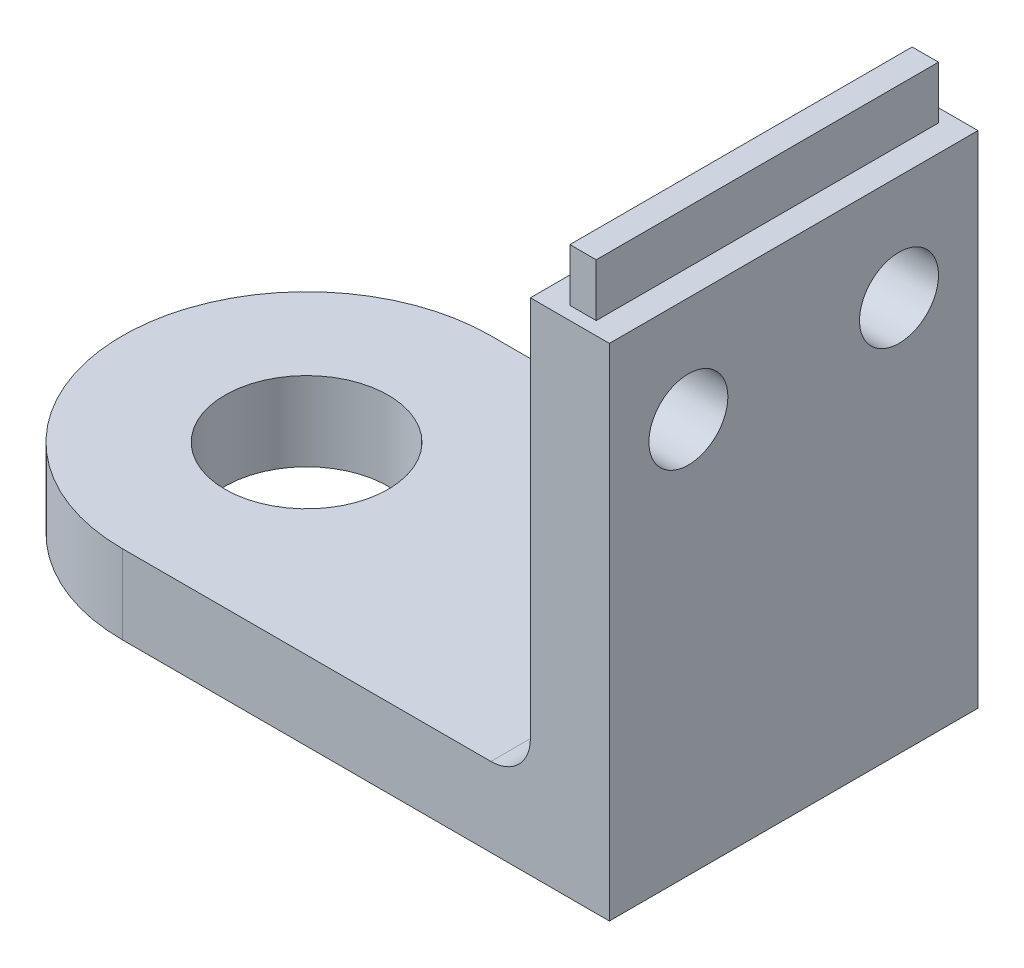
SolidWorks part; units mm, degrees
material "ABS"
ref_plane "Front Plane" through (0, 0, 0) normal (0, 0, 1) x (1, 0, 0)
ref_plane "Top Plane" through (0, 0, 0) normal (0, 1, 0) x (1, 0, 0)
ref_plane "Right Plane" through (0, 0, 0) normal (1, 0, 0) x (0, 0, -1)
ref_plane "Y-19_00" through (0, -19, 0) normal (0, 1, 0) x (1, 0, 0)
sketch "Sketch1" plane through (0, -19, 0) normal (0, 1, 0) x (1, 0, 0)
  line L0 (5.5, -7) -> (24, -7)
  line L1 (24, -7) -> (24, 7)
  line L2 (24, 7) -> (5.5, 7)
  arc A0 (5.5, 7) -> (5.5, -7) centre (5.5, 0) ccw
extrude "Boss-Extrude1" add sketch "Sketch1" along normal blind 3
sketch "Sketch2" plane through (0, 0, 0) normal (0, 0, 1) x (1, 0, 0)
  line L0 (7.7, -19) -> (-7.7, -19) construction
  line L1 (21, -19) -> (24, -19)
  line L2 (21, -19) -> (21, 0)
  line L3 (21, 0) -> (24, 0)
  line L4 (24, -19) -> (24, 0)
extrude "Boss-Extrude2" add sketch "Sketch2" along normal mid plane 14
sketch "Sketch3" plane through (0, 0, 0) normal (0, 1, 0) x (1, 0, 0)
  line L1 (22, -6.5) -> (23, -6.5)
  line L2 (22, -6.5) -> (22, 6.5)
  line L3 (22, 6.5) -> (23, 6.5)
  line L4 (23, -6.5) -> (23, 6.5)
extrude "Boss-Extrude3" add sketch "Sketch3" along normal blind 2
sketch "Sketch4" plane through (0, -19, 0) normal (0, 1, 0) x (1, 0, 0)
  circle A0 centre (5.5, 0) radius 3.1
extrude "Cut-Extrude2" cut sketch "Sketch4" along normal blind 3
ref_plane "X_LINK" through (24, 0, 0) normal (1, 0, 0) x (0, 0, -1)
sketch "Sketch5" plane through (24, 0, 0) normal (1, 0, 0) x (0, 0, -1)
  circle A0 centre (-4, -4) radius 1.5
  circle A1 centre (4, -4) radius 1.5
extrude "Cut-Extrude3" cut sketch "Sketch5" against normal blind 3
fillet "Fillet1" radius 1.5 1 edges at (21, -16, 0)
